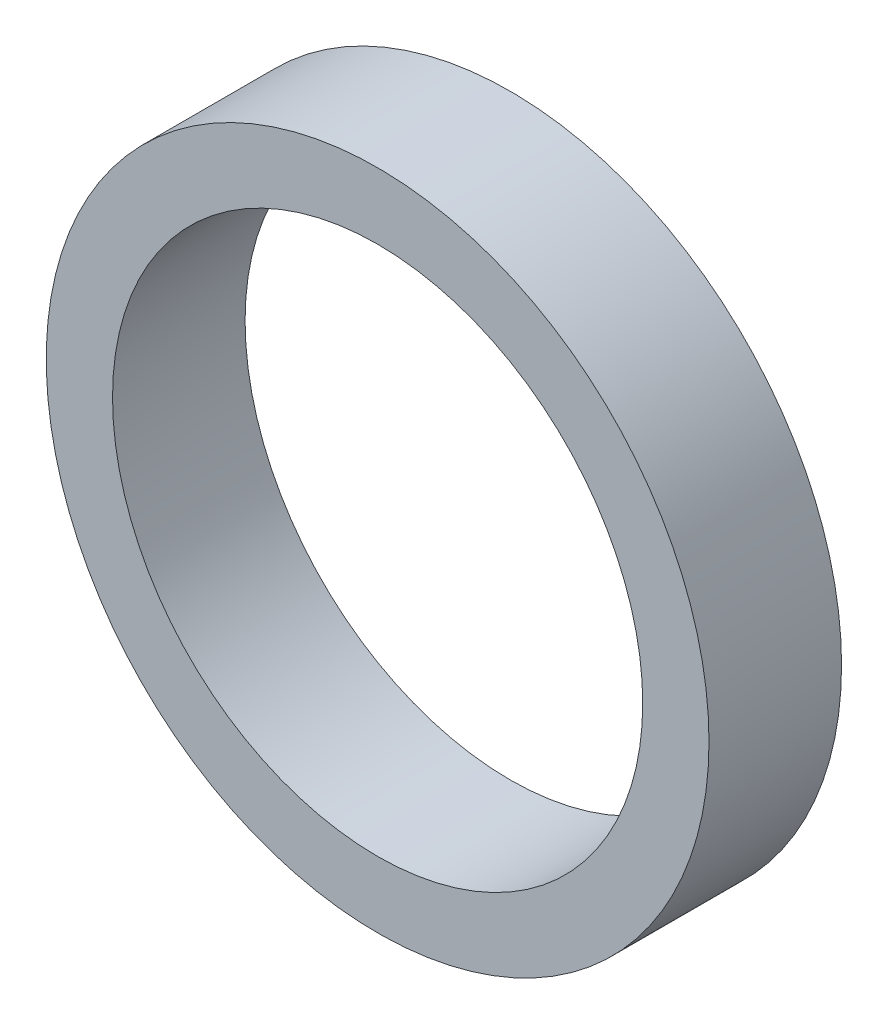
SolidWorks part; units mm, degrees
ref_plane "Front Plane" through (0, 0, 0) normal (0, 0, 1) x (1, 0, 0)
ref_plane "Top Plane" through (0, 0, 0) normal (0, 1, 0) x (1, 0, 0)
ref_plane "Right Plane" through (0, 0, 0) normal (1, 0, 0) x (0, 0, -1)
sketch "Sketch1" plane through (0, 0, 0) normal (0, 0, 1) x (1, 0, 0)
  circle A0 centre (0, 0) radius 31.75
  circle A1 centre (0, 0) radius 25.4
extrude "Boss-Extrude1" add sketch "Sketch1" along normal blind 12.7
